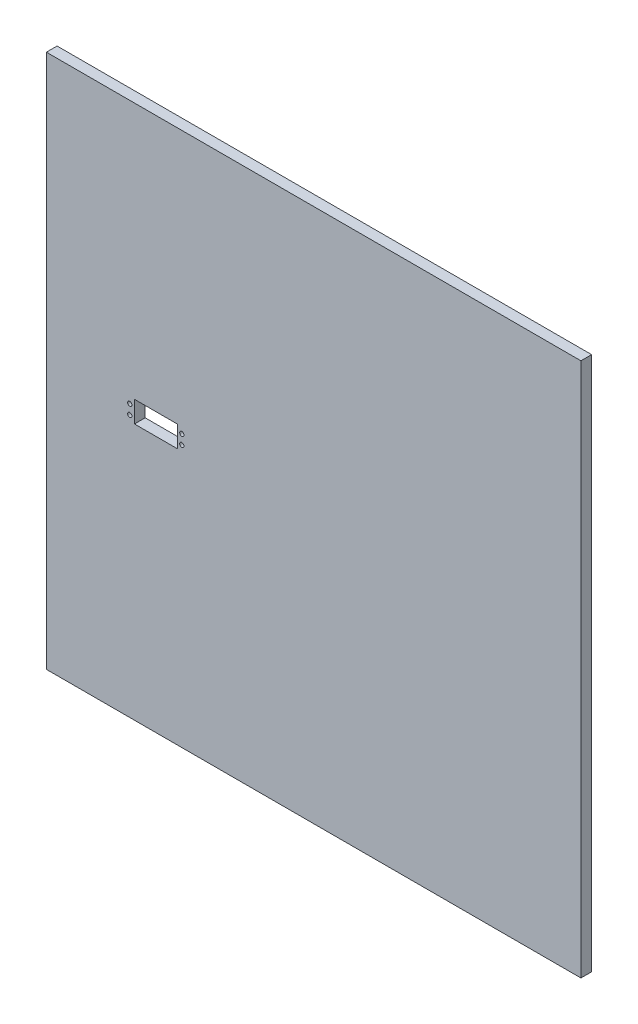
SolidWorks part; units mm, degrees
ref_plane "Alzado" through (0, 0, 0) normal (0, 0, 1) x (1, 0, 0)
ref_plane "Planta" through (0, 0, 0) normal (0, 1, 0) x (1, 0, 0)
ref_plane "Vista lateral" through (0, 0, 0) normal (1, 0, 0) x (0, 0, -1)
sketch "Croquis1" plane through (0, 0, 0) normal (0, 0, 1) x (1, 0, 0)
  line L1 (-250, -250) -> (250, -250)
  line L2 (-250, -250) -> (-250, 250)
  line L3 (-250, 250) -> (250, 250)
  line L4 (250, -250) -> (250, 250)
  line L5 (-250, -250) -> (250, 250) construction
  line L6 (-250, 250) -> (250, -250) construction
  line L7 (-127.3, 10) -> (-167.6, 10)
  line L8 (-127.3, 10) -> (-127.3, -10)
  line L9 (-127.3, -10) -> (-167.6, -10)
  line L10 (-167.6, 10) -> (-167.6, -10)
  line L11 (-127.3, 10) -> (-167.6, -10) construction
  line L12 (-127.3, -10) -> (-167.6, 10) construction
  circle A0 centre (-172.0197, -4.8419) radius 2
  circle A1 centre (-172.0197, 4.1581) radius 2
  circle A2 centre (-123.3131, 4.1581) radius 2
  circle A3 centre (-123.3131, -4.8419) radius 2
  circle A5 centre (-138, 0) radius 1.27 construction
  point P0 (0, 0)
  point P6 (-138, 0)
  dimension "D5" = 10
  dimension "D6" = 10.7
  dimension "D1" = 500
  dimension "D2" = 500
  dimension "D3" = 40.3
  dimension "D4" = 20
extrude "Saliente-Extruir1" add sketch "Croquis1" along normal blind 10
